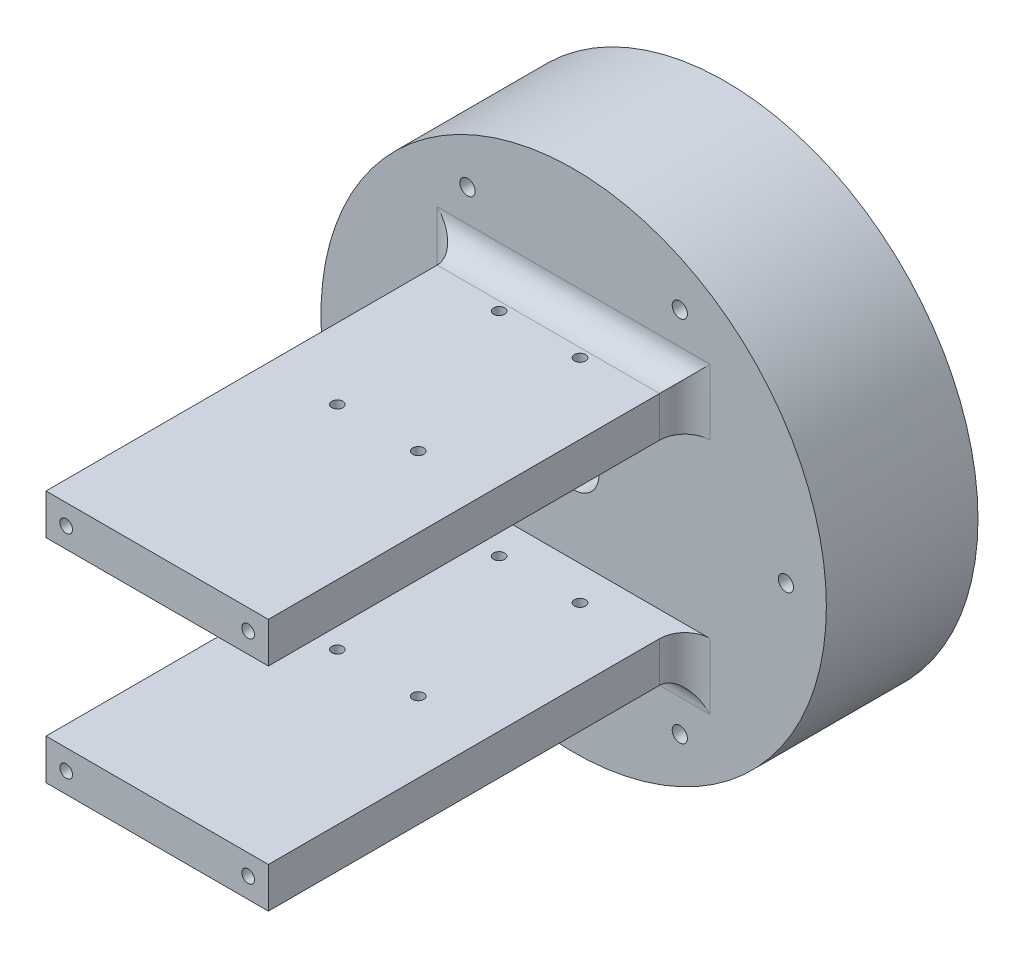
SolidWorks part; units mm, degrees
ref_plane "Alzado" through (0, 0, 0) normal (0, 0, 1) x (1, 0, 0)
ref_plane "Planta" through (0, 0, 0) normal (0, 1, 0) x (1, 0, 0)
ref_plane "Vista lateral" through (0, 0, 0) normal (1, 0, 0) x (0, 0, -1)
sketch "Croquis1" plane through (0, 0, 0) normal (0, 0, 1) x (1, 0, 0)
  circle A0 centre (0, 0) radius 50
  dimension "D1" = 100
extrude "Saliente-Extruir1" add sketch "Croquis1" along normal blind 30
sketch "Croquis2" plane through (0, 0, 0) normal (0, 0, -1) x (-1, 0, 0)
  circle A0 centre (0, 0) radius 40.25
  dimension "D1" = 80.5
extrude "Cortar-Extruir1" cut sketch "Croquis2" against normal blind 10.5
sketch "Croquis3" plane through (0, 0, 10.5) normal (0, 0, -1) x (-1, 0, 0)
  circle A0 centre (0, 0) radius 21.5
  dimension "D1" = 43
extrude "Saliente-Extruir2" add sketch "Croquis3" along normal blind 12.9
sketch "Croquis4" plane through (0, 0, -2.4) normal (0, 0, -1) x (-1, 0, 0)
  arc A0 (3.3385, 5.6934) -> (0.6686, 6.566) centre (0, 0) ccw construction
  arc A1 (-0.6686, -6.566) -> (1.6652, -6.3865) centre (0.5063, -6.5805) ccw
  arc A2 (-5.1157, -4.1701) -> (-3.3385, -5.6934) centre (-4.2951, -5.0112) ccw
  arc A3 (-6.566, 0.6686) -> (-6.3865, -1.6652) centre (-6.5805, -0.5063) ccw
  arc A4 (-4.1701, 5.1157) -> (-5.6934, 3.3385) centre (-5.0112, 4.2951) ccw
  arc A5 (0.6686, 6.566) -> (-1.6652, 6.3865) centre (-0.5063, 6.5805) ccw
  arc A6 (5.1157, 4.1701) -> (3.3385, 5.6934) centre (4.2951, 5.0112) ccw
  arc A7 (6.566, -0.6686) -> (6.3865, 1.6652) centre (6.5805, 0.5063) ccw
  arc A8 (4.1701, -5.1157) -> (5.6934, -3.3385) centre (5.0112, -4.2951) ccw
  arc A9 (3.3385, 5.6934) -> (0.6686, 6.566) centre (0, 0) ccw
  arc A10 (6.3865, 1.6652) -> (5.1157, 4.1701) centre (0, 0) ccw construction
  arc A11 (6.3865, 1.6652) -> (5.1157, 4.1701) centre (0, 0) ccw
  arc A12 (5.6934, -3.3385) -> (6.566, -0.6686) centre (0, 0) ccw construction
  arc A13 (5.6934, -3.3385) -> (6.566, -0.6686) centre (0, 0) ccw
  arc A14 (1.6652, -6.3865) -> (4.1701, -5.1157) centre (0, 0) ccw construction
  arc A15 (1.6652, -6.3865) -> (4.1701, -5.1157) centre (0, 0) ccw
  arc A16 (-3.3385, -5.6934) -> (-0.6686, -6.566) centre (0, 0) ccw construction
  arc A17 (-3.3385, -5.6934) -> (-0.6686, -6.566) centre (0, 0) ccw
  arc A18 (-6.3865, -1.6652) -> (-5.1157, -4.1701) centre (0, 0) ccw construction
  arc A19 (-6.3865, -1.6652) -> (-5.1157, -4.1701) centre (0, 0) ccw
  arc A20 (-5.6934, 3.3385) -> (-6.566, 0.6686) centre (0, 0) ccw construction
  arc A21 (-5.6934, 3.3385) -> (-6.566, 0.6686) centre (0, 0) ccw
  arc A22 (-1.6652, 6.3865) -> (-4.1701, 5.1157) centre (0, 0) ccw construction
  arc A23 (-1.6652, 6.3865) -> (-4.1701, 5.1157) centre (0, 0) ccw
  dimension "D1" = 13.2
  dimension "D2" = 2.35
  dimension "D3" = 8
extrude "Cortar-Extruir2" cut sketch "Croquis4" against normal blind 12.9
sketch "Croquis7" plane through (0, 0, 30) normal (0, 0, 1) x (1, 0, 0)
  line L0 (-50, 0) -> (50, 0) construction
  line L1 (22, -25) -> (-22, -25)
  line L2 (22, -25) -> (22, -17)
  line L11 (22, -17) -> (-22, -17)
  line L12 (-22, -25) -> (-22, -17)
  line L13 (22, 17) -> (-22, 17)
  line L14 (22, 17) -> (22, 25)
  line L15 (22, 25) -> (-22, 25)
  line L16 (-22, 17) -> (-22, 25)
  line L17 (0, 50) -> (0, -50) construction
  circle A1 centre (0, 0) radius 50 construction
  point P15 (0, 17)
  dimension "D1" = 8
  dimension "D2" = 44
  dimension "D3" = 8
  dimension "D4" = 44
  dimension "D5" = 34
  dimension "D6" = 17
  dimension "D7" = 28
extrude "Saliente-Extruir3" add sketch "Croquis7" along normal blind 82.4
fillet "Redondeo1" radius 5 6 edges at (-22, 21, 30) (0, 25, 30) (22, 21, 30) (22, -21, 30) (-22, -21, 30) (0, -25, 30)
sketch "Croquis8" plane through (0, -25, 0) normal (0, -1, 0) x (1, 0, 0)
  line L0 (-22, 112.4) -> (-22, 35) construction
  line L1 (50, 30) -> (-50, 30) construction
  circle A0 centre (-8, 36.75) radius 1.1
  circle A1 centre (8, 36.75) radius 1.1
  circle A2 centre (-8, 68.75) radius 1.1
  circle A3 centre (8, 68.75) radius 1.1
  dimension "D1" = 2.2
  dimension "D2" = 14
  dimension "D3" = 6.75
  dimension "D4" = 32
  dimension "D5" = 16
extrude "Cortar-Extruir3" cut sketch "Croquis8" against normal up to surface (50 mm away) up to face at (0, 25, 73.7)
sketch "Croquis9" plane through (0, 0, 30) normal (0, 0, 1) x (1, 0, 0)
  circle A0 centre (0, 0) radius 42 construction
  circle A1 centre (-42, 0) radius 1.5
  circle A2 centre (-21, 36.3731) radius 1.5
  circle A3 centre (21, 36.3731) radius 1.5
  circle A4 centre (42, 0) radius 1.5
  circle A5 centre (21, -36.3731) radius 1.5
  circle A6 centre (-21, -36.3731) radius 1.5
  dimension "D1" = 84
  dimension "D2" = 3
extrude "Cortar-Extruir4" cut sketch "Croquis9" against normal blind 7
sketch "Croquis11" plane through (0, 0, 112.4) normal (0, 0, 1) x (1, 0, 0)
  line L0 (-22, 25) -> (-22, 17) construction
  line L1 (22, 25) -> (-22, 25) construction
  line L2 (22, 17) -> (22, 25) construction
  line L4 (22, -17) -> (-22, -17) construction
  circle A0 centre (-18, -21) radius 1.25
  circle A1 centre (18, -21) radius 1.25
  circle A2 centre (-18, 21) radius 1.25
  circle A3 centre (18, 21) radius 1.25
  dimension "D1" = 2.5
  dimension "D2" = 4
  dimension "D3" = 4
  dimension "D4" = 4
  dimension "D5" = 4
extrude "Cortar-Extruir5" cut sketch "Croquis11" against normal blind 15
sketch "Croquis12" plane through (0, 0, 10.5) normal (0, 0, -1) x (-1, 0, 0)
  circle A0 centre (0, 0) radius 40.25
  circle A1 centre (0, 0) radius 37.68
  dimension "D1" = 80.5
  dimension "D2" = 75.36
extrude "Saliente-Extruir4" add sketch "Croquis12" along normal up to surface (10.5 mm away) up to face at (-40.25, 0, 0)
sketch "Croquis13" plane through (0, 0, 10.5) normal (0, 0, -1) x (-1, 0, 0)
  circle A0 centre (0, 0) radius 5
  dimension "D1" = 10
extrude "Cortar-Extruir6" cut sketch "Croquis13" against normal up to next
sketch "Croquis14" plane through (0, 0, 30) normal (0, 0, 1) x (1, 0, 0)
  line L0 (-27, 17) -> (-27, 30) construction
  line L1 (0, -5) -> (-27, -5)
  line L2 (0, -5) -> (0, 5)
  line L3 (0, 5) -> (-27, 5)
  line L4 (-27, -5) -> (-27, 5)
  circle A0 centre (0, 0) radius 5 construction
  dimension "D1" = 27
extrude "Cortar-Extruir7" cut sketch "Croquis14" against normal blind 5
sketch "Croquis15" plane through (0, 0, 10.5) normal (0, 0, -1) x (-1, 0, 0)
  circle A0 centre (0, 0) radius 35
  circle A1 centre (0, 0) radius 21.5
  dimension "D1" = 70
  dimension "D2" = 43
extrude "Cortar-Extruir8" cut sketch "Croquis15" against normal blind 2.5
